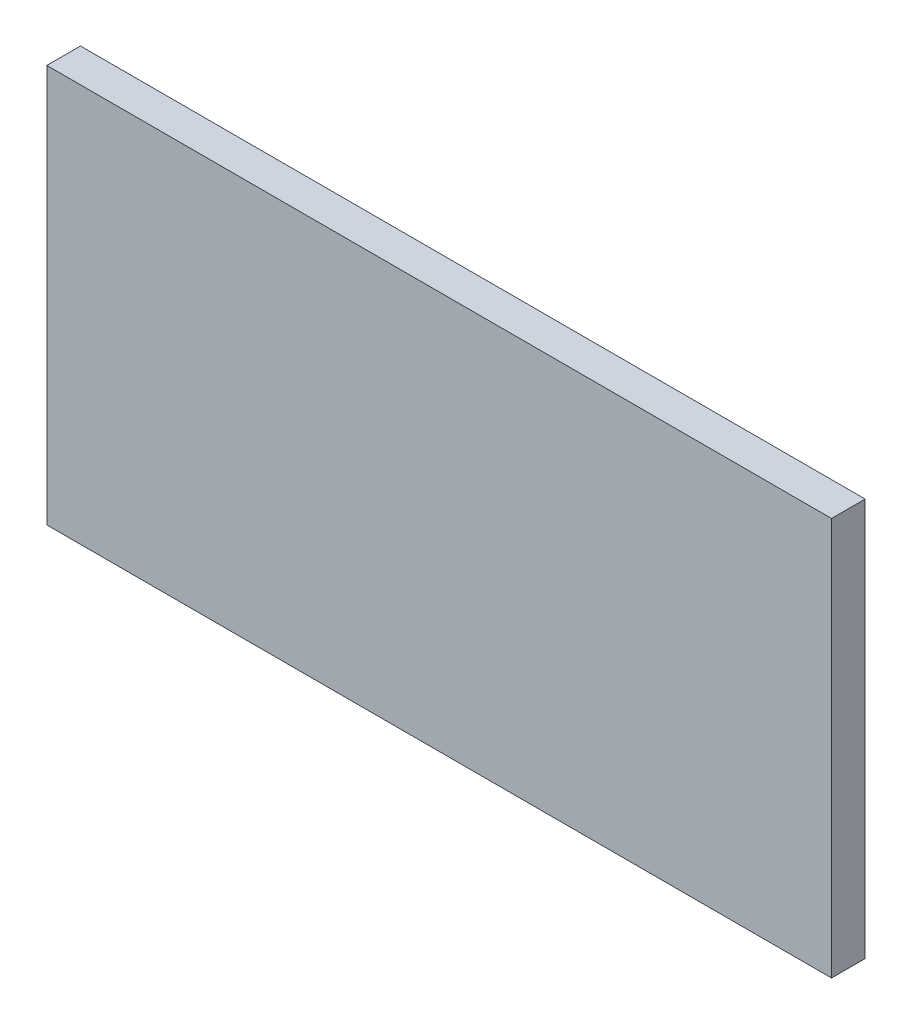
SolidWorks part; units mm, degrees
ref_plane "Front Plane" through (0, 0, 0) normal (0, 0, 1) x (1, 0, 0)
ref_plane "Top Plane" through (0, 0, 0) normal (0, 1, 0) x (1, 0, 0)
ref_plane "Right Plane" through (0, 0, 0) normal (1, 0, 0) x (0, 0, -1)
sketch "Sketch1" plane through (0, 0, 0) normal (0, 0, 1) x (1, 0, 0)
  line L1 (700, -355) -> (-700, -355)
  line L2 (700, -355) -> (700, 355)
  line L3 (700, 355) -> (-700, 355)
  line L4 (-700, -355) -> (-700, 355)
  line L5 (700, -355) -> (-700, 355) construction
  line L6 (700, 355) -> (-700, -355) construction
  point P0 (0, 0)
  dimension "D1" = 1400
  dimension "D2" = 710
extrude "Boss-Extrude1" add sketch "Sketch1" along normal blind 60
